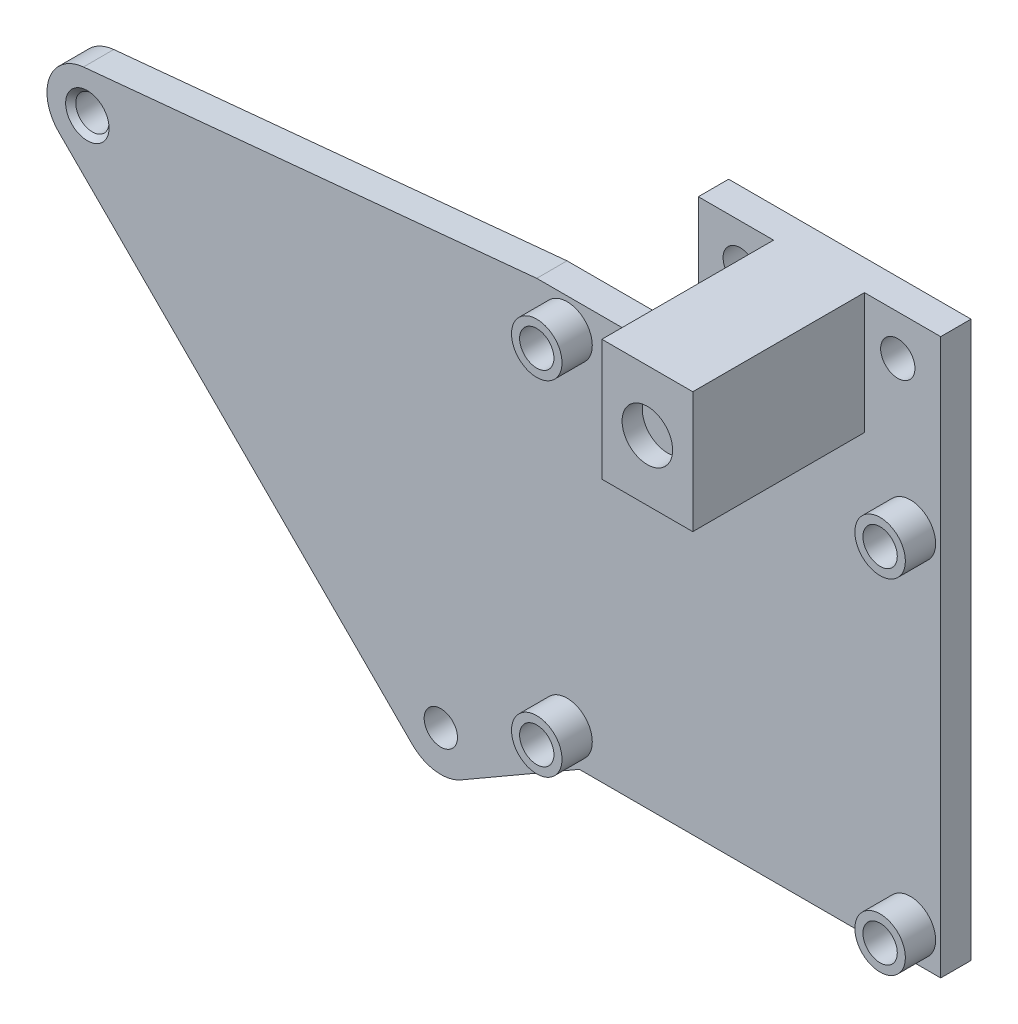
SolidWorks part; units mm, degrees
ref_plane "Front Plane" through (0, 0, 0) normal (0, 0, 1) x (1, 0, 0)
ref_plane "Top Plane" through (0, 0, 0) normal (0, 1, 0) x (1, 0, 0)
ref_plane "Right Plane" through (0, 0, 0) normal (1, 0, 0) x (0, 0, -1)
sketch "Sketch1" plane through (0, 0, 0) normal (0, 0, 1) x (1, 0, 0)
  line L2 (20, 20) -> (20, -20)
  line L3 (20, -20) -> (-15.7842, -20)
  line L5 (20, 20) -> (-20, -20) construction
  line L6 (20, -20) -> (-20, 20) construction
  line L7 (17, 17) -> (-17, 17) construction
  line L8 (17, 17) -> (17, -17) construction
  line L9 (17, -17) -> (-17, -17) construction
  line L10 (-17, 17) -> (-17, -17) construction
  line L11 (17, 17) -> (-17, -17) construction
  line L12 (17, -17) -> (-17, 17) construction
  line L13 (20, 35) -> (-4, 35)
  line L14 (-4, 35) -> (-4, 20)
  line L15 (-4, 20) -> (-20, 20)
  line L16 (-4, 31) -> (19.9, 31) construction
  line L17 (-64.8831, 15.6816) -> (-20, 20)
  line L19 (-20, -20) -> (-20, 20) construction
  line L20 (20, 20) -> (20, 35)
  line L21 (-4, 20) -> (20, 20) construction
  line L22 (-27.5, -26.7641) -> (-15.7842, -20)
  line L23 (-67.3284, 8.8716) -> (-32.3284, -26.1284)
  circle A0 centre (-17, 17) radius 1.7
  circle A1 centre (17, 17) radius 1.7
  circle A2 centre (17, -17) radius 1.7
  circle A3 centre (-17, -17) radius 1.7
  circle A4 centre (0.15, 31) radius 1.7
  circle A5 centre (15.75, 31) radius 1.7
  circle A7 centre (-64.5, 11.7) radius 1.65
  arc A8 (-64.8831, 15.6816) -> (-67.3284, 8.8716) centre (-64.5, 11.7) ccw
  circle A10 centre (-29.5, -23.3) radius 1.65
  arc A11 (-32.3284, -26.1284) -> (-27.5, -26.7641) centre (-29.5, -23.3) ccw
  point P0 (0, 0)
  point P5 (0, 0)
  point P25 (7.95, 31)
  point P28 (-64.5, 11.7)
  point P33 (-20, -19.3252)
  point P34 (0, 0)
  point P35 (0, 0)
  point P36 (-8.9278, -20)
  dimension "D4" = 3.4
  dimension "D5" = 3.4
  dimension "D6" = 3.4
  dimension "D7" = 3.4
  dimension "D12" = 7.8
  dimension "D14" = 3.4
  dimension "D15" = 3.4
  dimension "D16" = 35
  dimension "D17" = 35
  dimension "D18" = 3.3
  dimension "D21" = 3.3
  dimension "D22" = 8
  dimension "D23" = 150
  dimension "D9" = 4.15
  dimension "D19" = 81.5
  dimension "D26" = 8
  dimension "D2" = 40
  dimension "D3" = 34
  dimension "D8" = 15
  dimension "D10" = 24
  dimension "D11" = 4
  dimension "D13" = 7.8
  dimension "D20" = 8.3
  dimension "D24" = 34
  dimension "D25" = 3
extrude "Boss-Extrude1" add sketch "Sketch1" along normal blind 3
chamfer "Chamfer2" distance 0.5 angle 45 1 edges at (-62.85, 11.7, 3)
sketch "Sketch2" plane through (0, 0, 3) normal (0, 0, 1) x (1, 0, 0)
  line L0 (20, 35) -> (-4, 35) construction
  line L1 (3.45, 35) -> (12.45, 35)
  line L2 (3.45, 35) -> (3.45, 23)
  line L3 (3.45, 23) -> (12.45, 23)
  line L4 (12.45, 35) -> (12.45, 23)
  circle A0 centre (0.15, 31) radius 1.7 construction
  dimension "D3" = 3.3
  dimension "D1" = 12
  dimension "D2" = 9
extrude "Boss-Extrude2" add sketch "Sketch2" along normal blind 17
sketch "Sketch3" plane through (0, 0, 20) normal (0, 0, 1) x (1, 0, 0)
  line L0 (3.45, 23) -> (12.45, 35) construction
  circle A0 centre (7.95, 29) radius 2.5
  dimension "D1" = 5
extrude "Cut-Extrude1" cut sketch "Sketch3" against normal blind 2
sketch "Sketch4" plane through (0, 0, 3) normal (0, 0, 1) x (1, 0, 0)
  circle A0 centre (-17, 17) radius 1.7
  circle A1 centre (-17, 17) radius 2.5
  circle A2 centre (17, 17) radius 1.7
  circle A3 centre (17, 17) radius 2.5
  circle A4 centre (-17, -17) radius 2.5
  circle A5 centre (-17, -17) radius 1.7
  circle A6 centre (17, -17) radius 1.7
  circle A7 centre (17, -17) radius 2.5
  circle A8 centre (-17, 17) radius 1.7 construction
  circle A9 centre (17, 17) radius 1.7 construction
  circle A10 centre (-17, -17) radius 1.7 construction
  circle A11 centre (17, -17) radius 1.7 construction
  dimension "D1" = 5
  dimension "D2" = 5
  dimension "D3" = 5
  dimension "D4" = 5
extrude "Boss-Extrude3" add sketch "Sketch4" along normal blind 3
